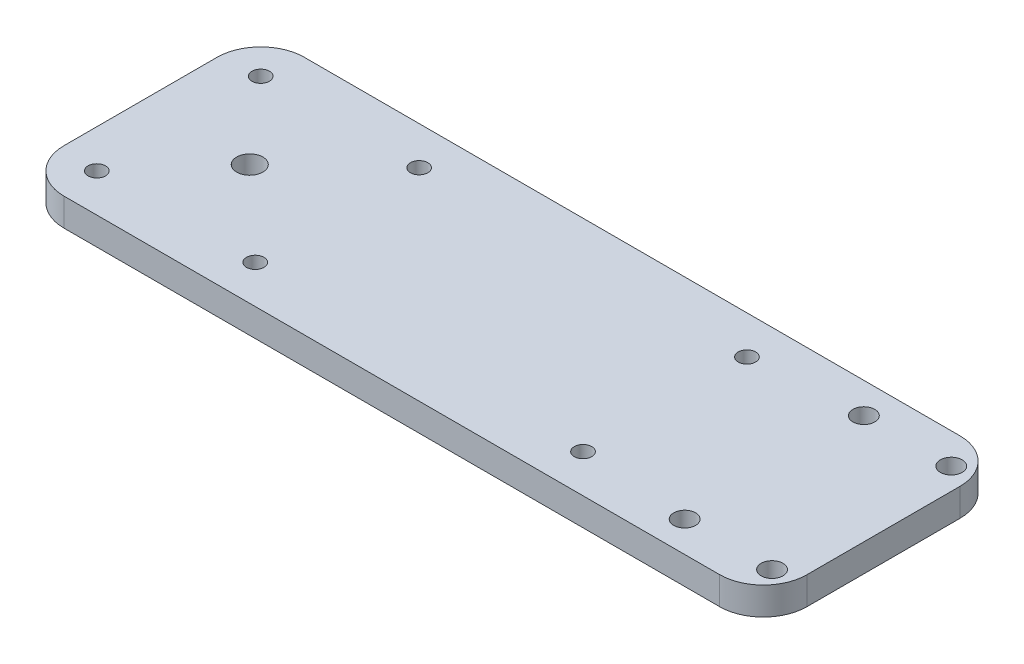
SolidWorks part; units mm, degrees
ref_plane "Front Plane" through (0, 0, 0) normal (0, 0, 1) x (1, 0, 0)
ref_plane "Top Plane" through (0, 0, 0) normal (0, 1, 0) x (1, 0, 0)
ref_plane "Right Plane" through (0, 0, 0) normal (1, 0, 0) x (0, 0, -1)
sketch "Sketch1" plane through (0, 0, 0) normal (0, 1, 0) x (1, 0, 0)
  line L0 (-25, 0) -> (0, 0) construction
  line L1 (-25, 27.5) -> (145, 27.5)
  line L2 (-25, 27.5) -> (-25, -27.5)
  line L3 (-25, -27.5) -> (145, -27.5)
  line L4 (145, 27.5) -> (145, -27.5)
  point P7 (125, 0)
  dimension "D1" = 55
  dimension "D2" = 125
  dimension "D3" = 20
  dimension "D4" = 25
extrude "Boss-Extrude1" add sketch "Sketch1" along normal blind 6.35
fillet "Fillet1" radius 10 4 edges at (-25, 3.175, 27.5) (-25, 3.175, -27.5) (145, 3.175, -27.5) (145, 3.175, 27.5)
hole_wizard "Ø6.0mm Dowel Hole1" positions "Sketch3" profile "Sketch4" hole size "Ø6.0" standard "DIN" end condition up to next
sketch "Sketch3" plane through (0, 6.35, 0) normal (0, 1, 0) x (1, 0, 0)
  point P0 (0, 0)
sketch "Sketch4" plane through (0, 6.35, 0) normal (1, 0, 0) x (0, 0, 1)
  line L0 (0, 0) -> (0, 6.35)
  line L1 (0, 6.35) -> (3, 6.35)
  line L2 (3, 6.35) -> (3, 0)
  line L5 (3, 0) -> (0, 0)
  line L11 (0, -6.35) -> (0, 107.95) construction
  dimension "Thru Hole Dia." = 6
  dimension "Thru Hole Depth" = 6.35
hole_wizard "Ø4.0mm Dowel Hole1" positions "Sketch5" profile "Sketch6" hole size "Ø4.0" standard "DIN" end condition up to next
sketch "Sketch5" plane through (0, 6.35, 0) normal (0, 1, 0) x (1, 0, 0)
  line L0 (-25, 17.5) -> (-25, -17.5) construction
  line L1 (-15, -27.5) -> (135, -27.5) construction
  line L3 (-25, 0) -> (145, 0) construction
  line L4 (145, -17.5) -> (145, 17.5) construction
  circle A0 centre (0, 0) radius 3 construction
  point P0 (-16.25, -18.75)
  point P2 (20, -18.75)
  point P15 (95, -18.75)
  point P16 (170, -18.75)
  point P25 (170, 18.75)
  point P26 (95, 18.75)
  point P27 (20, 18.75)
  point P28 (-16.25, 18.75)
  dimension "D3" = 20
  dimension "D1" = 8.75
  dimension "D2" = 8.75
  dimension "D5" = 75
  dimension "D4" = 3
sketch "Sketch6" plane through (-16.25, 6.35, 18.75) normal (1, 0, 0) x (0, 0, 1)
  line L0 (0, 0) -> (0, 6.35)
  line L1 (0, 6.35) -> (2, 6.35)
  line L2 (2, 6.35) -> (2, 0)
  line L5 (2, 0) -> (0, 0)
  line L11 (0, -6.35) -> (0, 107.95) construction
  dimension "Thru Hole Dia." = 4
  dimension "Thru Hole Depth" = 6.35
hole_wizard "Ø5.0mm Dowel Hole1" positions "Sketch7" profile "Sketch8" hole size "Ø5.0" standard "DIN" end condition through all
sketch "Sketch7" plane through (0, 6.35, 0) normal (0, 1, 0) x (1, 0, 0)
  line L0 (130, 27.5) -> (130, -27.5) construction
  line L1 (135, 27.5) -> (-15, 27.5) construction
  line L2 (-15, -27.5) -> (135, -27.5) construction
  line L4 (145, -17.5) -> (145, 17.5) construction
  line L5 (145, 0) -> (-25, 0) construction
  line L6 (-25, 17.5) -> (-25, -17.5) construction
  point P0 (140, 20.5)
  point P20 (120, 20.5)
  point P21 (140, -20.5)
  point P22 (120, -20.5)
  dimension "D1" = 15
  dimension "D2" = 5
  dimension "D3" = 7
sketch "Sketch8" plane through (140, 6.35, -20.5) normal (1, 0, 0) x (0, 0, 1)
  line L0 (0, 0) -> (0, 6.35)
  line L1 (0, 6.35) -> (2.5, 6.35)
  line L2 (2.5, 6.35) -> (2.5, 0)
  line L5 (2.5, 0) -> (0, 0)
  line L11 (0, -6.35) -> (0, 107.95) construction
  dimension "Thru Hole Dia." = 5
  dimension "Thru Hole Depth" = 6.35
equation "\"Pivot to Pivot Distance\" = 125mm"
equation "\"D2@Sketch1\"=\"Pivot to Pivot Distance\""
equation "\"Plate Thickness\"= 0.25in"
equation "\"D1@Boss-Extrude1\"=\"Plate Thickness\""
